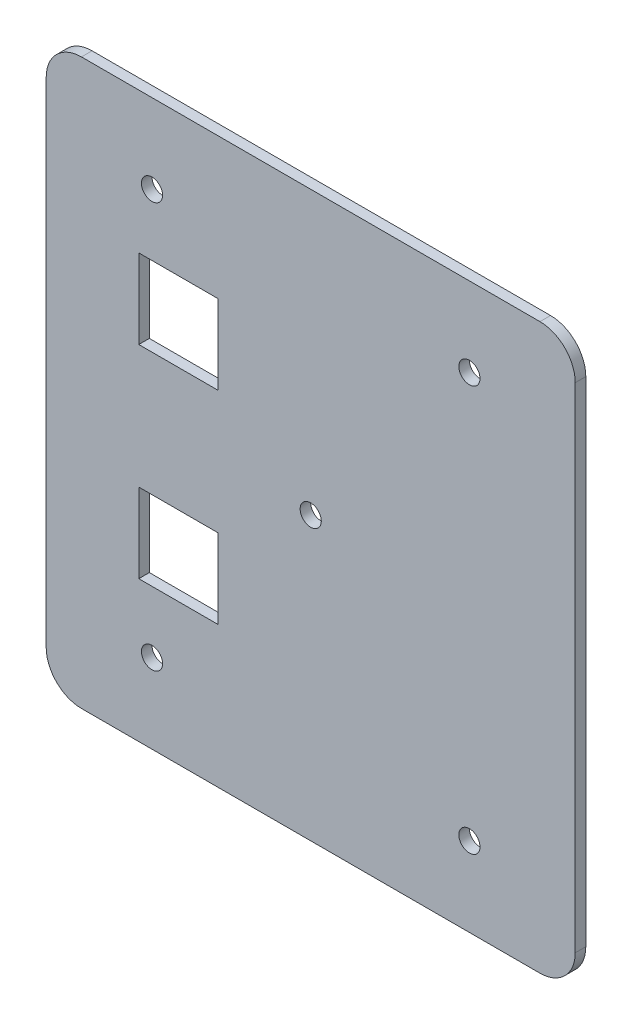
SolidWorks part; units mm, degrees
ref_plane "Front Plane" through (0, 0, 0) normal (0, 0, 1) x (1, 0, 0)
ref_plane "Top Plane" through (0, 0, 0) normal (0, 1, 0) x (1, 0, 0)
ref_plane "Right Plane" through (0, 0, 0) normal (1, 0, 0) x (0, 0, -1)
sketch "Sketch1" plane through (0, 0, 0) normal (0, 0, 1) x (1, 0, 0)
  line L0 (-22.5, -22.5) -> (22.5, -22.5) construction
  line L1 (22.5, -22.5) -> (22.5, 22.5) construction
  line L2 (22.5, 22.5) -> (-22.5, 22.5) construction
  line L3 (-22.5, 22.5) -> (-22.5, -22.5) construction
  line L4 (22.5, 92.5) -> (22.5, 137.5) construction
  line L5 (22.5, 137.5) -> (-22.5, 137.5) construction
  line L6 (-22.5, 137.5) -> (-22.5, 92.5) construction
  line L7 (-22.5, 92.5) -> (22.5, 92.5) construction
  line L8 (-22.5, -22.5) -> (22.5, -22.5)
  line L9 (22.5, -22.5) -> (22.5, 22.5)
  line L10 (22.5, 22.5) -> (-22.5, 22.5)
  line L11 (-22.5, 22.5) -> (-22.5, -22.5)
  line L12 (22.5, 92.5) -> (22.5, 137.5)
  line L13 (22.5, 137.5) -> (-22.5, 137.5)
  line L14 (-22.5, 137.5) -> (-22.5, 92.5)
  line L15 (-22.5, 92.5) -> (22.5, 92.5)
  line L16 (-22.5, 92.5) -> (22.5, 137.5)
  line L17 (-22.5, 137.5) -> (22.5, 92.5)
  line L18 (22.5, 22.5) -> (-22.5, -22.5)
  line L19 (-22.5, 22.5) -> (22.5, -22.5)
  line L20 (75, -102.5) -> (75, 57.5)
  line L21 (-55, -102.5) -> (75, -102.5)
  line L22 (-75, -82.5) -> (-75, 197.5)
  line L23 (75, -102.5) -> (75, 217.5)
  line L24 (-55, 217.5) -> (75, 217.5)
  line L25 (-75, -102.5) -> (75, 217.5) construction
  line L26 (75, -102.5) -> (-75, 217.5) construction
  line L27 (0, 0) -> (0, 57.5)
  line L28 (75, -102.5) -> (75, 217.5)
  line L29 (75, -102.5) -> (205, -102.5)
  line L30 (75, 217.5) -> (205, 217.5)
  line L31 (225, -82.5) -> (225, 197.5)
  line L32 (165, 217.5) -> (165, 172.5)
  line L33 (165, 172.5) -> (225, 172.5)
  line L34 (225, -57.5) -> (165, -57.5)
  line L35 (165, -57.5) -> (165, -102.5)
  line L36 (-15, -102.5) -> (-15, -57.5)
  line L37 (-15, -57.5) -> (-75, -57.5)
  line L38 (-75, 172.5) -> (-15, 172.5)
  line L39 (-15, 172.5) -> (-15, 217.5)
  circle A0 centre (-15, 172.5) radius 6
  circle A1 centre (165, 172.5) radius 6
  circle A2 centre (165, -57.5) radius 6
  circle A3 centre (-15, -57.5) radius 6
  circle A4 centre (75, 57.5) radius 6
  arc A5 (-75, -82.5) -> (-55, -102.5) centre (-55, -82.5) ccw
  arc A6 (205, -102.5) -> (225, -82.5) centre (205, -82.5) ccw
  arc A7 (205, 217.5) -> (225, 197.5) centre (205, 197.5) cw
  arc A8 (-75, 197.5) -> (-55, 217.5) centre (-55, 197.5) cw
  point P7 (0, 57.5)
  point P43 (225, 217.5)
  dimension "D7" = 12
  dimension "D8" = 160
  dimension "D9" = 20
  dimension "D1" = 150
  dimension "D2" = 320
  dimension "D3" = 57.5
  dimension "D4" = 150
  dimension "D5" = 60
  dimension "D6" = 45
extrude "Boss-Extrude1" add sketch "Sketch1" along normal blind 6
